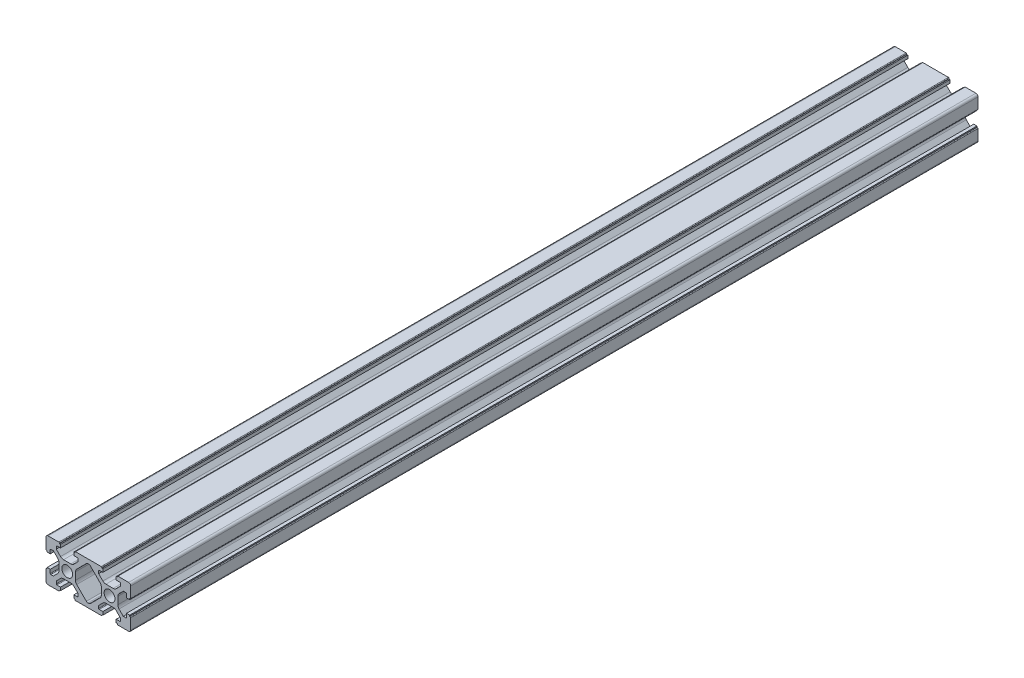
SolidWorks part; units mm, degrees
material "6063-T5"
ref_plane "Alzado" through (0, 0, 0) normal (0, 0, 1) x (1, 0, 0)
ref_plane "Planta" through (0, 0, 0) normal (0, 1, 0) x (1, 0, 0)
ref_plane "Vista lateral" through (0, 0, 0) normal (1, 0, 0) x (0, 0, -1)
sketch "Croquis1" plane through (0, 0, 0) normal (0, 0, 1) x (1, 0, 0)
  line L0 (-20, -9) -> (-20, -3.95)
  line L1 (-19.7, -3.65) -> (-19.5, -3.65)
  line L2 (-19.5, -3.65) -> (-19.5, -3.15)
  line L3 (-19.5, -3.15) -> (-18, -3.15)
  line L4 (-18, -3.15) -> (-18, -4.85)
  line L5 (-13.9, -1.7216) -> (-13.9, 1.7216)
  line L6 (-18, 3.15) -> (-18, 4.85)
  line L7 (-19.5, 3.15) -> (-18, 3.15)
  line L8 (-19.5, 3.65) -> (-19.5, 3.15)
  line L9 (-19.7, 3.65) -> (-19.5, 3.65)
  line L10 (-20, 9) -> (-20, 3.95)
  line L11 (-17.7, 5.15) -> (-16.5, 5.15)
  line L12 (-16.5, 5.15) -> (-14.4858, 3.1358)
  line L13 (-16.5, -5.15) -> (-14.4858, -3.1358)
  line L14 (-17.7, -5.15) -> (-16.5, -5.15)
  line L15 (-4.85, 7.7) -> (-4.85, 6.5)
  line L16 (-4.85, 6.5) -> (-6.8642, 4.4858)
  line L17 (-15.15, 6.5) -> (-13.1358, 4.4858)
  line L18 (-15.15, 7.7) -> (-15.15, 6.5)
  line L19 (-19, 10) -> (-13.95, 10)
  line L20 (-13.65, 9.7) -> (-13.65, 9.5)
  line L21 (-13.65, 9.5) -> (-13.15, 9.5)
  line L22 (-13.15, 9.5) -> (-13.15, 8)
  line L23 (-13.15, 8) -> (-14.85, 8)
  line L24 (-8.2784, 3.9) -> (-11.7216, 3.9)
  line L25 (-6.85, 8) -> (-5.15, 8)
  line L26 (-6.85, 9.5) -> (-6.85, 8)
  line L27 (-6.35, 9.5) -> (-6.85, 9.5)
  line L28 (-6.35, 9.7) -> (-6.35, 9.5)
  line L29 (-6.1, 1.7216) -> (-6.1, -1.7216)
  line L30 (-3.5, 5.15) -> (-5.5142, 3.1358)
  line L31 (-15.15, -7.7) -> (-15.15, -6.5)
  line L32 (-15.15, -6.5) -> (-13.1358, -4.4858)
  line L33 (-4.85, -6.5) -> (-6.8642, -4.4858)
  line L34 (-4.85, -7.7) -> (-4.85, -6.5)
  line L35 (0, -10) -> (-6.05, -10)
  line L36 (-6.35, -9.7) -> (-6.35, -9.5)
  line L37 (-6.35, -9.5) -> (-6.85, -9.5)
  line L38 (-6.85, -9.5) -> (-6.85, -8)
  line L39 (-6.85, -8) -> (-5.15, -8)
  line L40 (-11.7216, -3.9) -> (-8.2784, -3.9)
  line L41 (-13.15, -8) -> (-14.85, -8)
  line L42 (-13.15, -9.5) -> (-13.15, -8)
  line L43 (-13.65, -9.5) -> (-13.15, -9.5)
  line L44 (-13.65, -9.7) -> (-13.65, -9.5)
  line L45 (-19, -10) -> (-13.95, -10)
  line L46 (6.1, -1.7216) -> (6.1, 1.7216)
  line L47 (3.5, 5.15) -> (5.5142, 3.1358)
  line L48 (15.15, 7.7) -> (15.15, 6.5)
  line L49 (15.15, 6.5) -> (13.1358, 4.4858)
  line L50 (4.85, 6.5) -> (6.8642, 4.4858)
  line L51 (4.85, 7.7) -> (4.85, 6.5)
  line L52 (6.35, 9.7) -> (6.35, 9.5)
  line L53 (6.35, 9.5) -> (6.85, 9.5)
  line L54 (6.85, 9.5) -> (6.85, 8)
  line L55 (6.85, 8) -> (5.15, 8)
  line L56 (11.7216, 3.9) -> (8.2784, 3.9)
  line L57 (13.15, 8) -> (14.85, 8)
  line L58 (13.15, 9.5) -> (13.15, 8)
  line L59 (13.65, 9.5) -> (13.15, 9.5)
  line L60 (13.65, 9.7) -> (13.65, 9.5)
  line L61 (19, 10) -> (13.95, 10)
  line L62 (20, 9) -> (20, 3.95)
  line L63 (19.7, 3.65) -> (19.5, 3.65)
  line L64 (19.5, 3.65) -> (19.5, 3.15)
  line L65 (19.5, 3.15) -> (18, 3.15)
  line L66 (18, 3.15) -> (18, 4.85)
  line L67 (13.9, 1.7216) -> (13.9, -1.7216)
  line L68 (18, -3.15) -> (18, -4.85)
  line L69 (19.5, -3.15) -> (18, -3.15)
  line L70 (19.5, -3.65) -> (19.5, -3.15)
  line L71 (19.7, -3.65) -> (19.5, -3.65)
  line L72 (20, -9) -> (20, -3.95)
  line L73 (17.7, -5.15) -> (16.5, -5.15)
  line L74 (16.5, -5.15) -> (14.4858, -3.1358)
  line L75 (16.5, 5.15) -> (14.4858, 3.1358)
  line L76 (17.7, 5.15) -> (16.5, 5.15)
  line L77 (4.85, -7.7) -> (4.85, -6.5)
  line L78 (4.85, -6.5) -> (6.8642, -4.4858)
  line L79 (15.15, -6.5) -> (13.1358, -4.4858)
  line L80 (15.15, -7.7) -> (15.15, -6.5)
  line L81 (19, -10) -> (13.65, -10)
  line L82 (13.65, -10) -> (13.65, -9.5)
  line L83 (13.65, -9.5) -> (13.15, -9.5)
  line L84 (13.15, -9.5) -> (13.15, -8)
  line L85 (13.15, -8) -> (14.85, -8)
  line L86 (8.2784, -3.9) -> (11.7216, -3.9)
  line L87 (6.85, -8) -> (5.15, -8)
  line L88 (6.85, -9.5) -> (6.85, -8)
  line L89 (6.35, -9.5) -> (6.85, -9.5)
  line L90 (6.35, -9.7) -> (6.35, -9.5)
  line L91 (0, -10) -> (6.05, -10)
  line L92 (-3.5, 5.15) -> (-0.9429, 7.7071)
  line L93 (3.5, 5.15) -> (0.9429, 7.7071)
  line L94 (-0.2358, 8) -> (0.2358, 8)
  line L95 (-6.05, 10) -> (6.05, 10)
  line L96 (-0.2358, -8) -> (0.2358, -8)
  line L97 (3.5, -5.15) -> (0.9429, -7.7071)
  line L98 (-3.5, -5.15) -> (-0.9429, -7.7071)
  line L99 (-3.5, -5.15) -> (-5.5142, -3.1358)
  line L100 (3.5, -5.15) -> (5.5142, -3.1358)
  arc A0 (-5.15, -8) -> (-4.85, -7.7) centre (-5.15, -7.7) ccw
  arc A1 (-15.15, -7.7) -> (-14.85, -8) centre (-14.85, -7.7) ccw
  arc A2 (-18, -4.85) -> (-17.7, -5.15) centre (-17.7, -4.85) ccw
  arc A3 (-17.7, 5.15) -> (-18, 4.85) centre (-17.7, 4.85) ccw
  arc A4 (-14.85, 8) -> (-15.15, 7.7) centre (-14.85, 7.7) ccw
  arc A5 (-4.85, 7.7) -> (-5.15, 8) centre (-5.15, 7.7) ccw
  arc A6 (-19.7, -3.65) -> (-20, -3.95) centre (-19.7, -3.95) ccw
  arc A7 (-20, 3.95) -> (-19.7, 3.65) centre (-19.7, 3.95) ccw
  arc A8 (-20, -9) -> (-19, -10) centre (-19, -9) ccw
  arc A9 (-19, 10) -> (-20, 9) centre (-19, 9) ccw
  circle A10 centre (-10, 0) radius 2.55
  arc A11 (-13.9, 1.7216) -> (-14.4858, 3.1358) centre (-15.9, 1.7216) ccw
  arc A12 (-14.4858, -3.1358) -> (-13.9, -1.7216) centre (-15.9, -1.7216) ccw
  arc A13 (-8.2784, 3.9) -> (-6.8642, 4.4858) centre (-8.2784, 5.9) ccw
  arc A14 (-13.1358, 4.4858) -> (-11.7216, 3.9) centre (-11.7216, 5.9) ccw
  arc A15 (-6.1, -1.7216) -> (-5.5142, -3.1358) centre (-4.1, -1.7216) ccw
  arc A16 (-5.5142, 3.1358) -> (-6.1, 1.7216) centre (-4.1, 1.7216) ccw
  arc A17 (-11.7216, -3.9) -> (-13.1358, -4.4858) centre (-11.7216, -5.9) ccw
  arc A18 (-6.8642, -4.4858) -> (-8.2784, -3.9) centre (-8.2784, -5.9) ccw
  arc A19 (17.7, -5.15) -> (18, -4.85) centre (17.7, -4.85) ccw
  arc A20 (14.85, -8) -> (15.15, -7.7) centre (14.85, -7.7) ccw
  arc A21 (4.85, -7.7) -> (5.15, -8) centre (5.15, -7.7) ccw
  arc A22 (5.15, 8) -> (4.85, 7.7) centre (5.15, 7.7) ccw
  arc A23 (15.15, 7.7) -> (14.85, 8) centre (14.85, 7.7) ccw
  arc A24 (18, 4.85) -> (17.7, 5.15) centre (17.7, 4.85) ccw
  arc A25 (20, -3.95) -> (19.7, -3.65) centre (19.7, -3.95) ccw
  arc A26 (19.7, 3.65) -> (20, 3.95) centre (19.7, 3.95) ccw
  arc A27 (19, -10) -> (20, -9) centre (19, -9) ccw
  arc A28 (20, 9) -> (19, 10) centre (19, 9) ccw
  circle A29 centre (10, 0) radius 2.55
  arc A30 (6.1, 1.7216) -> (5.5142, 3.1358) centre (4.1, 1.7216) ccw
  arc A31 (5.5142, -3.1358) -> (6.1, -1.7216) centre (4.1, -1.7216) ccw
  arc A32 (11.7216, 3.9) -> (13.1358, 4.4858) centre (11.7216, 5.9) ccw
  arc A33 (6.8642, 4.4858) -> (8.2784, 3.9) centre (8.2784, 5.9) ccw
  arc A34 (13.9, -1.7216) -> (14.4858, -3.1358) centre (15.9, -1.7216) ccw
  arc A35 (14.4858, 3.1358) -> (13.9, 1.7216) centre (15.9, 1.7216) ccw
  arc A36 (8.2784, -3.9) -> (6.8642, -4.4858) centre (8.2784, -5.9) ccw
  arc A37 (13.1358, -4.4858) -> (11.7216, -3.9) centre (11.7216, -5.9) ccw
  arc A38 (-0.2358, 8) -> (-0.9429, 7.7071) centre (-0.2358, 7) ccw
  arc A39 (0.9429, 7.7071) -> (0.2358, 8) centre (0.2358, 7) ccw
  arc A40 (0.2358, -8) -> (0.9429, -7.7071) centre (0.2358, -7) ccw
  arc A41 (-0.9429, -7.7071) -> (-0.2358, -8) centre (-0.2358, -7) ccw
  arc A42 (6.05, -10) -> (6.35, -9.7) centre (6.05, -9.7) ccw
  arc A43 (-6.35, -9.7) -> (-6.05, -10) centre (-6.05, -9.7) ccw
  arc A44 (-13.95, -10) -> (-13.65, -9.7) centre (-13.95, -9.7) ccw
  arc A45 (13.95, 10) -> (13.65, 9.7) centre (13.95, 9.7) ccw
  arc A46 (6.35, 9.7) -> (6.05, 10) centre (6.05, 9.7) ccw
  arc A47 (-6.05, 10) -> (-6.35, 9.7) centre (-6.05, 9.7) ccw
  arc A48 (-13.65, 9.7) -> (-13.95, 10) centre (-13.95, 9.7) ccw
  point P199 (-20, 6.475)
  dimension "D1" = 20
  dimension "D2" = 40
extrude "Saliente-Extruir1" add sketch "Croquis1" along normal blind 400 contours A10 | L98 A41 L96 A40 L97 L100 A31 L46 A30 L47 L93 A39 L94 A38 L92 L30 A16 L29 A15 L99 | A29 | L19 A48 L20 L21 L22 L23 A4 L18 L17 A14 L24 A13 L16 L15 A5 L25 L26 L27 L28 A47 L95 A46 L52 L53 L54 L55 A22 L51 L50 A33 L56 A32 L49 L48 A23 L57 L58 L59 L60 A45 L61 A28 L62 A26 L63 L64 L65 L66 A24 L76 L75 A35 L67 A34 L74 L73 A19 L68 L69 L70 L71 A25 L72 A27 L81 L82 L83 L84 L85 A20 L80 L79 A37 L86 A36 L78 L77 A21 L87 L88 L89 L90 A42 L91 L35 A43 L36 L37 L38 L39 A0 L34 L33 A18 L40 A17 L32 L31 A1 L41 L42 L43 L44 A44 L45 A8 L0 A6 L1 L2 L3 L4 A2 L14 L13 A12 L5 A11 L12 L11 A3 L6 L7 L8 L9 A7 L10 A9
